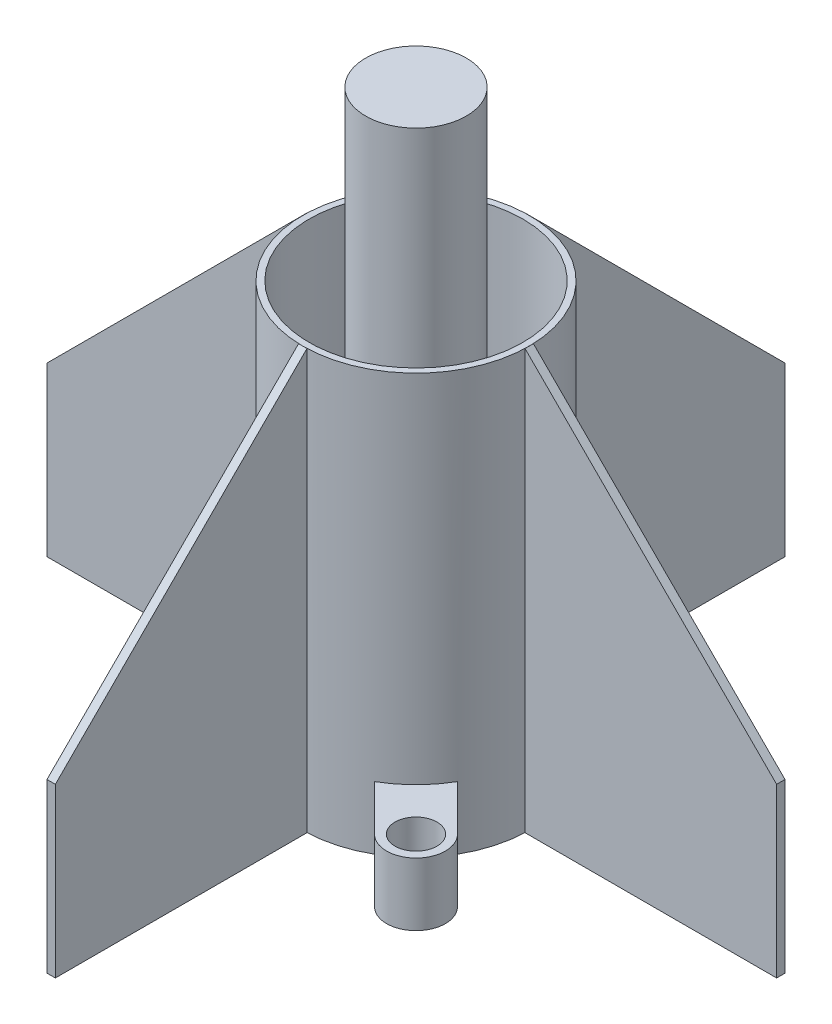
SolidWorks part; units mm, degrees
ref_plane "Front Plane" through (0, 0, 0) normal (0, 0, 1) x (1, 0, 0)
ref_plane "Top Plane" through (0, 0, 0) normal (0, 1, 0) x (1, 0, 0)
ref_plane "Right Plane" through (0, 0, 0) normal (1, 0, 0) x (0, 0, -1)
sketch "Sketch1" plane through (0, 0, 0) normal (0, 1, 0) x (1, 0, 0)
  circle A0 centre (0, 0) radius 27
  dimension "D1" = 54
extrude "Boss-Extrude1" add sketch "Sketch1" along normal blind 100
sketch "Sketch2" plane through (0, 0, 0) normal (0, 0, 1) x (1, 0, 0)
  line L0 (27, 100) -> (87, 40)
  line L1 (87, 40) -> (87, 0)
  line L2 (87, 0) -> (27, 0)
  line L3 (27, 0) -> (27, 100)
  line L4 (0, -77) -> (0, 77) construction
  line L5 (-87, 0) -> (-27, 0)
  line L6 (-87, 40) -> (-87, 0)
  line L7 (-27, 100) -> (-87, 40)
  line L8 (-27, 0) -> (-27, 100)
  dimension "D1" = 60
  dimension "D2" = 40
extrude "Boss-Extrude2" add sketch "Sketch2" along normal mid plane 2 separate body
sketch "Sketch3" plane through (0, 0, 0) normal (1, 0, 0) x (0, 0, -1)
  line L0 (-27, 100) -> (-87, 40)
  line L1 (-87, 40) -> (-87, 0)
  line L2 (-87, 0) -> (-27, 0)
  line L3 (-27, 0) -> (-27, 100)
  line L4 (0, 77) -> (0, -77) construction
  line L5 (27, 0) -> (27, 100)
  line L6 (87, 0) -> (27, 0)
  line L7 (87, 40) -> (87, 0)
  line L8 (27, 100) -> (87, 40)
  dimension "D1" = 60
  dimension "D2" = 40
extrude "Boss-Extrude3" add sketch "Sketch3" along normal mid plane 2 separate body
sketch "Sketch4" plane through (0, 0, 0) normal (0, -1, 0) x (-1, 0, 0)
  circle A0 centre (0, 0) radius 25.5
  dimension "D1" = 51
extrude "Cut-Extrude1" cut sketch "Sketch4" against normal through all
sketch "Sketch9" plane through (0, 0, 0) normal (0, -1, 0) x (1, 0, 0)
  circle A0 centre (0, 0) radius 27
extrude "Boss-Extrude6" add sketch "Sketch9" against normal blind 4
sketch "Sketch10" plane through (0, 0, 0) normal (0, -1, 0) x (1, 0, 0)
  circle A0 centre (0, 0) radius 12
  dimension "D1" = 24
extrude "Boss-Extrude7" add sketch "Sketch10" against normal blind 140
sketch "Sketch11" plane through (0, 0, 0) normal (0, -1, 0) x (1, 0, 0)
  circle A0 centre (0, 0) radius 10.5
  dimension "D1" = 21
extrude "Cut-Extrude3" cut sketch "Sketch11" against normal blind 125
fillet "Fillet1" radius 10 1 edges at (0, 4, -12)
sketch "Sketch13" plane through (0, 0, 0) normal (0, -1, 0) x (1, 0, 0)
  line L0 (0, 0) -> (50.3848, 50.3848) construction
  line L1 (27, 1) -> (87, 1) construction
  line L2 (13.4893, 23.3888) -> (24.3334, 34.2328)
  line L3 (23.3888, 13.4893) -> (34.2328, 24.3334)
  line L4 (13.4893, 23.3888) -> (23.3888, 13.4893)
  line L5 (-49.4055, 49.4055) -> (49.4055, -49.4055) construction
  line L6 (-23.3888, -13.4893) -> (-34.2328, -24.3334)
  line L7 (-23.3888, -13.4893) -> (-13.4893, -23.3888)
  line L8 (-13.4893, -23.3888) -> (-24.3334, -34.2328)
  circle A0 centre (0, 0) radius 27 construction
  arc A1 (24.3334, 34.2328) -> (34.2328, 24.3334) centre (29.2831, 29.2831) cw
  arc A2 (-34.2328, -24.3334) -> (-24.3334, -34.2328) centre (-29.2831, -29.2831) ccw
  point P9 (18.4391, 18.4391)
  point P15 (0, 0)
  dimension "D1" = 45
  dimension "D2" = 14
  dimension "D3" = 42
extrude "Boss-Extrude8" add sketch "Sketch13" against normal blind 15
sketch "Sketch14" plane through (0, 0, 0) normal (0, -1, 0) x (1, 0, 0)
  line L0 (0, 0) -> (51.3613, -51.3613) construction
  line L1 (1, -27) -> (1, -87) construction
  line L2 (34.2328, 24.3334) -> (24.3334, 34.2328) construction
  circle A0 centre (29.2831, 29.2831) radius 5
  circle A1 centre (-29.2831, -29.2831) radius 5
  point P14 (29.2831, 29.2831)
  dimension "D2" = 10
  dimension "D1" = 45
extrude "Cut-Extrude4" cut sketch "Sketch14" against normal up to surface (15 mm away) up to face at (25.2617, 15, 25.2617)
